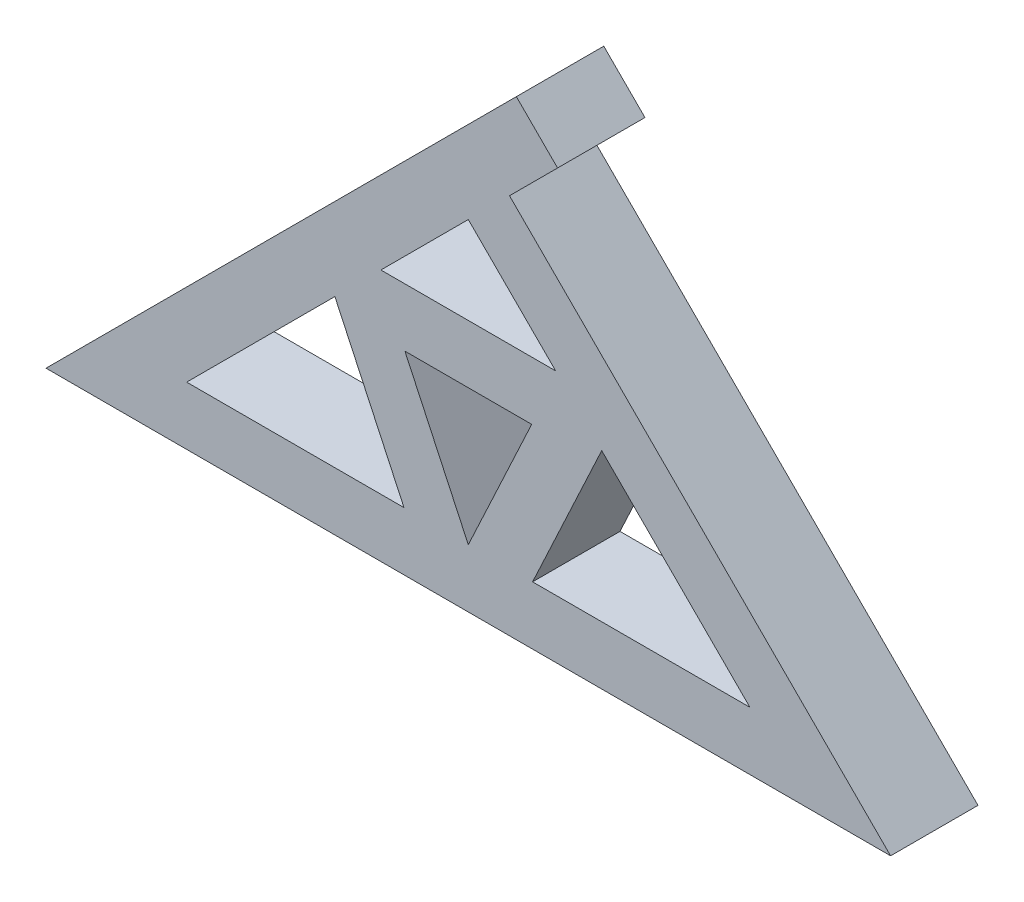
SolidWorks part; units mm, degrees
ref_plane "Front Plane" through (0, 0, 0) normal (0, 0, 1) x (1, 0, 0)
ref_plane "Top Plane" through (0, 0, 0) normal (0, 1, 0) x (1, 0, 0)
ref_plane "Right Plane" through (0, 0, 0) normal (1, 0, 0) x (0, 0, -1)
sketch "Sketch1" plane through (0, 0, 0) normal (0, 0, 1) x (1, 0, 0)
  line L0 (0, 0) -> (86.9741, 0)
  line L1 (86.9741, 0) -> (43.4871, 43.4871)
  line L2 (43.4871, 43.4871) -> (0, 0)
  line L3 (14.4853, 6) -> (43.4871, 35.0018)
  line L4 (43.4871, 35.0018) -> (72.4889, 6)
  line L5 (72.4889, 6) -> (14.4853, 6)
  line L6 (29.7491, 21.2639) -> (36.8668, 6)
  line L7 (34.4871, 26.0018) -> (52.4871, 26.0018)
  line L8 (57.225, 21.2639) -> (50.1073, 6)
  line L9 (43.4871, 6) -> (36.9579, 20.0018)
  line L10 (36.9579, 20.0018) -> (50.0162, 20.0018)
  line L11 (50.0162, 20.0018) -> (43.4871, 6)
  line L12 (43.4871, 6) -> (43.4871, 35.0018) construction
  dimension "D1" = 61.5
  dimension "D2" = 45
  dimension "D3" = 45
  dimension "D4" = 6
  dimension "D5" = 6
  dimension "D6" = 6
  dimension "D7" = 65
  dimension "D8" = 65
  dimension "D9" = 6
  dimension "D10" = 6
  dimension "D11" = 6
  dimension "D12" = 9
extrude "Boss-Extrude1" add sketch "Sketch1" along normal blind 9 contours L12 L10 L11 L5 L8 L4 L7 | L10 L12 L7 L3 L6 L5 L9 | L1 L2 L0 L4 L5 L3
sketch "Sketch2" plane through (0, 0, 0) normal (-0.7071, 0.7071, 0) x (0, 0, 1)
  line L0 (4.5, 0) -> (4.5, 61.5) construction
  line L1 (9, 0) -> (0, 0) construction
  line L2 (9, 61.5) -> (0, 61.5) construction
  line L3 (0, 61.5) -> (0, 68.5)
  line L4 (0, 68.5) -> (9, 68.5)
  line L5 (9, 68.5) -> (9, 61.5)
  line L6 (4.5, 61.5) -> (4.5, 65) construction
  circle A0 centre (4.5, 65) radius 1.625
  circle A1 centre (4.5, 9) radius 1.625
  dimension "D1" = 3.25
  dimension "D3" = 3.5
  dimension "D4" = 3.25
  dimension "D2" = 7
  dimension "D5" = 9
extrude "Cut-Extrude3" cut sketch "Sketch2" against normal blind 9 contours A1
sketch "Sketch8" plane through (0, 0, 0) normal (-0.7071, 0.7071, 0) x (0, 0, 1)
  line L0 (4.5, 0) -> (4.5, 61.5) construction
  line L1 (0, 61.5) -> (0, 68.5)
  line L2 (0, 68.5) -> (9, 68.5)
  line L3 (9, 68.5) -> (9, 61.5)
  line L4 (4.5, 61.5) -> (4.5, 65) construction
  line L5 (9, 0) -> (0, 0) construction
  line L6 (9, 61.5) -> (0, 61.5) construction
  circle A0 centre (4.5, 65) radius 1.625
  circle A1 centre (4.5, 4) radius 1.625
  line M6 (9, 61.5) -> (0, 61.5)
  dimension "D1" = 3.25
  dimension "D4" = 3.25
  dimension "D2" = 7
  dimension "D3" = 3.5
  dimension "D5" = 4
extrude "Boss-Extrude2" add sketch "Sketch8" against normal blind 6 contours L3 L2 L1 A0 M6
sketch "Sketch9" plane through (4.2426, -4.2426, 0) normal (0.7071, -0.7071, 0) x (0, 0, -1)
  circle A0 centre (-4.5, 65) radius 2.875
  circle A2 centre (-4.5, 9) radius 2.875
  dimension "D1" = 5.75
  dimension "D2" = 5.75
extrude "Cut-Extrude4" cut sketch "Sketch9" against normal blind 3 and the other way blind 33
